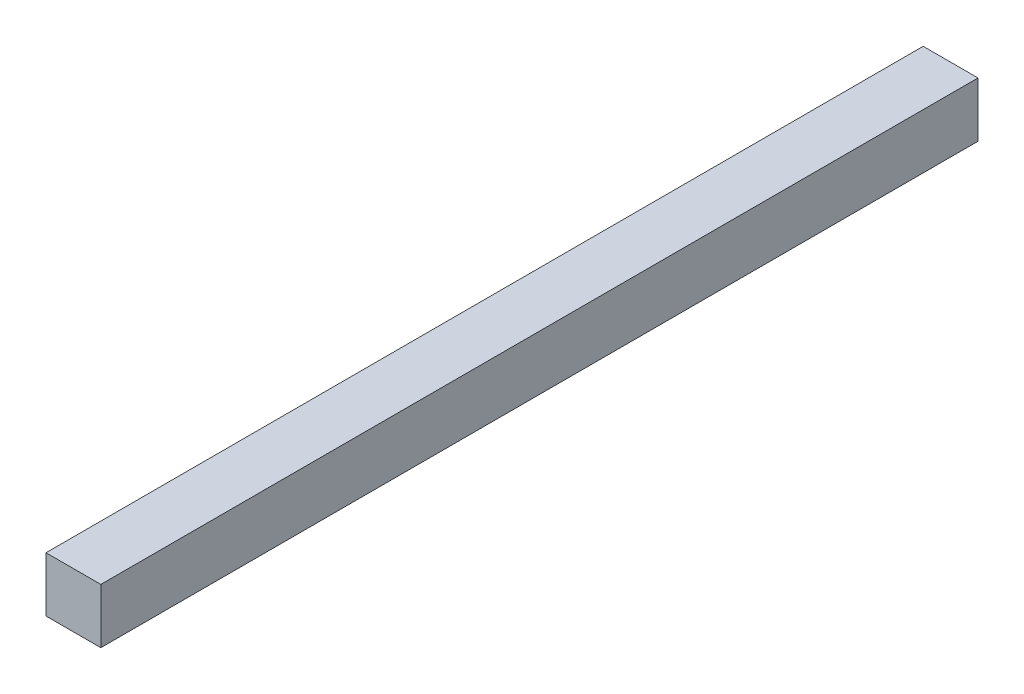
SolidWorks part; units mm, degrees
ref_plane "Front Plane" through (0, 0, 0) normal (0, 0, 1) x (1, 0, 0)
ref_plane "Top Plane" through (0, 0, 0) normal (0, 1, 0) x (1, 0, 0)
ref_plane "Right Plane" through (0, 0, 0) normal (1, 0, 0) x (0, 0, -1)
sketch "Sketch1" plane through (0, 0, 0) normal (0, 0, 1) x (1, 0, 0)
  line L1 (0, 0) -> (50, 0)
  line L2 (0, 0) -> (0, 50)
  line L3 (0, 50) -> (50, 50)
  line L4 (50, 0) -> (50, 50)
  dimension "D1" = 50
  dimension "D2" = 50
extrude "Boss-Extrude1" add sketch "Sketch1" along normal blind 800 contours L3 L4 L1 L2
